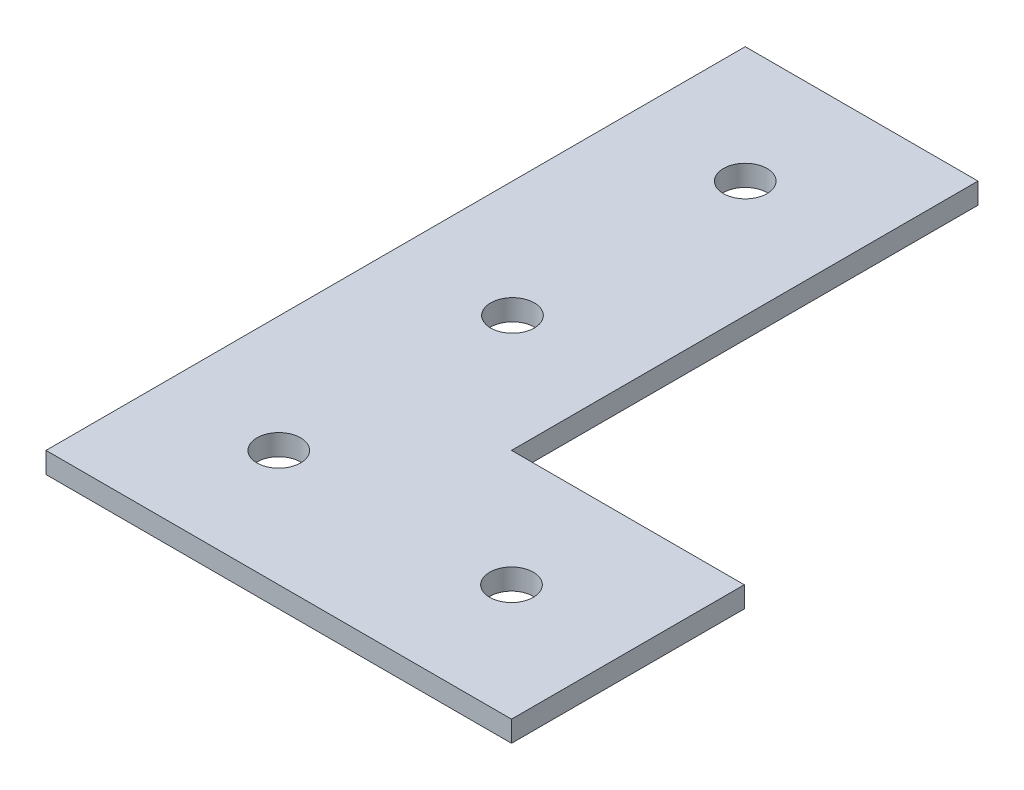
SolidWorks part; units mm, degrees
ref_plane "Front Plane" through (0, 0, 0) normal (0, 0, 1) x (1, 0, 0)
ref_plane "Top Plane" through (0, 0, 0) normal (0, 1, 0) x (1, 0, 0)
ref_plane "Right Plane" through (0, 0, 0) normal (1, 0, 0) x (0, 0, -1)
sketch "Sketch1" plane through (0, 0, 0) normal (0, 1, 0) x (1, 0, 0)
  line L0 (-25.4, 76.3048) -> (-25.4, 25.4)
  line L1 (0, 0) -> (-50.8, 0)
  line L2 (0, 0) -> (0, 25.4)
  line L3 (-25.4, 76.3048) -> (-50.8, 76.3048)
  line L4 (-50.8, 0) -> (-50.8, 76.3048)
  line L5 (-25.4, 25.4) -> (0, 25.4)
  dimension "D1" = 25.4
  dimension "D2" = 76.3048
  dimension "D3" = 25.4
  dimension "D4" = 50.8
extrude "Boss-Extrude1" add sketch "Sketch1" along normal blind 2.286
hole_wizard "3/16 (0.1875) Diameter Hole1" positions "Sketch3" profile "Sketch2" hole size "3/16" standard "ANSI Inch" end condition through all
sketch "Sketch3" plane through (0, 2.286, 0) normal (0, 1, 0) x (1, 0, 0)
  line L0 (-38.1, 76.3048) -> (-38.1, 0) construction
  line L1 (-25.4, 76.3048) -> (-50.8, 76.3048) construction
  line L2 (-50.8, 0) -> (0, 0) construction
  line L3 (0, 12.7) -> (-50.8, 12.7) construction
  line L4 (0, 0) -> (0, 25.4) construction
  line L5 (-50.8, 76.3048) -> (-50.8, 0) construction
  point P14 (-38.1, 63.6048)
  point P16 (-38.1, 38.2048)
  point P18 (-38.1, 12.7)
  point P20 (-12.7, 12.7)
  dimension "D1" = 12.7
  dimension "D2" = 12.7
  dimension "D3" = 38.1
sketch "Sketch2" plane through (-38.1, 2.286, -63.6048) normal (1, 0, 0) x (0, 0, 1)
  line L0 (0, 0) -> (0, 2.286)
  line L1 (0, 2.286) -> (2.3812, 2.286)
  line L2 (2.3812, 2.286) -> (2.3812, 0)
  line L5 (2.3812, 0) -> (0, 0)
  line L11 (0, -6.35) -> (0, 107.95) construction
  dimension "Thru Hole Dia." = 4.7625
  dimension "Thru Hole Depth" = 2.286
